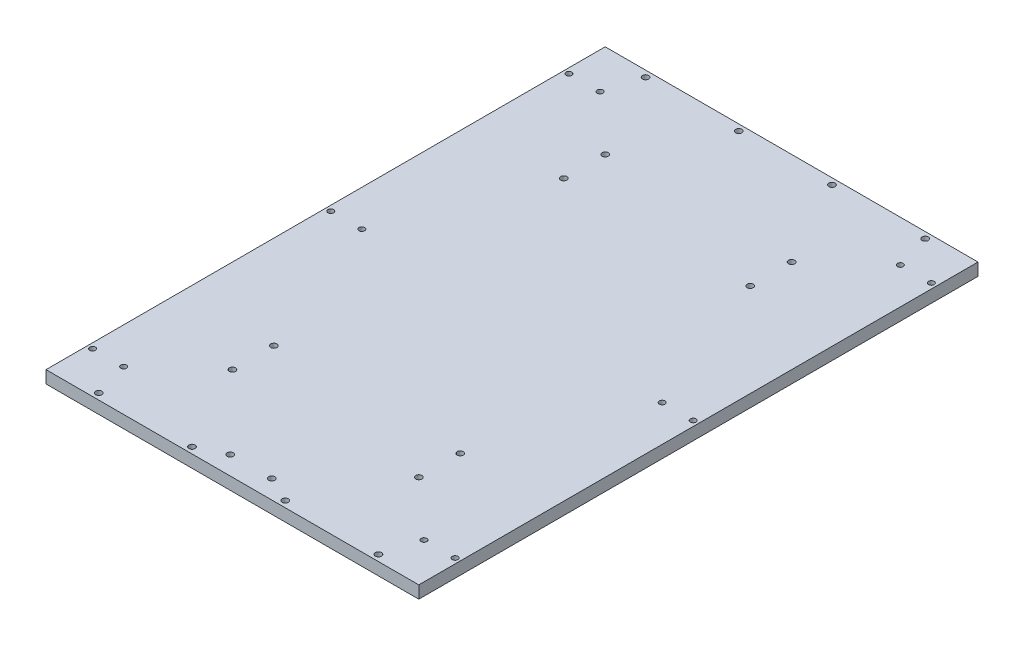
SolidWorks part; units mm, degrees
material "HDPE-green"
ref_plane "Front Plane" through (0, 0, 0) normal (0, 0, 1) x (1, 0, 0)
ref_plane "Top Plane" through (0, 0, 0) normal (0, 1, 0) x (1, 0, 0)
ref_plane "Right Plane" through (0, 0, 0) normal (1, 0, 0) x (0, 0, -1)
sketch "Sketch1" plane through (0, 0, 0) normal (0, 1, 0) x (1, 0, 0)
  line L1 (-180, -270) -> (180, -270)
  line L2 (-180, -270) -> (-180, 270)
  line L3 (-180, 270) -> (180, 270)
  line L4 (180, -270) -> (180, 270)
  line L5 (-180, -270) -> (180, 270) construction
  line L6 (-180, 270) -> (180, -270) construction
  point P0 (0, 0)
extrude "Boss-Extrude1" add sketch "Sketch1" along normal blind 12
sketch "Sketch2" plane through (0, 0, 0) normal (0, -1, 0) x (1, 0, 0)
  line L0 (-197.9035, 252) -> (209.2572, 252) construction
  line L1 (-180, 270) -> (180, 270) construction
  line L2 (0, 285.6833) -> (0, -295.2195) construction
  circle A0 centre (-20, 252) radius 3
  circle A1 centre (20, 252) radius 3
  dimension "D2" = 6
  dimension "D3" = 6
  dimension "D4" = 40
  dimension "D5" = 20
  dimension "D1" = 18
extrude "Cut-Extrude1" cut sketch "Sketch2" against normal up to next
sketch "Sketch3" plane through (0, 0, 0) normal (0, -1, 0) x (1, 0, 0)
  line L0 (-207.4551, 264) -> (223.7581, 264) construction
  line L1 (-180, 270) -> (180, 270) construction
  line L2 (180, 270) -> (180, -270) construction
  circle A0 centre (135, 264) radius 3
  dimension "D2" = 6
  dimension "D3" = 45
  dimension "D1" = 6
extrude "Cut-Extrude2" cut sketch "Sketch3" against normal up to next
pattern_linear "LPattern1" count 4 spacing 90 along (-1, 0, 0) of "Cut-Extrude2"
mirror "Mirror1" about plane through (0, 0, 0) normal (0, 0, 1) of "LPattern1", "Cut-Extrude2"
sketch "Sketch4" plane through (0, 12, 0) normal (0, 1, 0) x (1, 0, 0)
  line L0 (-160, 299.1839) -> (-160, -309.0635) construction
  line L1 (-180, 270) -> (-180, -270) construction
  line L2 (-188.5351, 0) -> (-124.846, 0) construction
  line L3 (-188.5351, 230) -> (-124.846, 230) construction
  line L4 (-129.91, -230) -> (-208.5429, -230) construction
  circle A0 centre (-175, 230) radius 2.75
  circle A1 centre (-145, 230) radius 2.75
  dimension "D4" = 5.5
  dimension "D5" = 5.5
  dimension "D7" = 15
  dimension "D1" = 20
  dimension "D2" = 230
  dimension "D3" = 230
  dimension "D6" = 15
extrude "Cut-Extrude3" cut sketch "Sketch4" against normal up to next
pattern_linear "LPattern2" count 3 spacing 230 along (0, 0, 1) of "Cut-Extrude3"
mirror "Mirror2" about plane through (0, 0, 0) normal (1, 0, 0) of "LPattern2", "Cut-Extrude3"
sketch "Sketch6" plane through (0, 12, 0) normal (0, 1, 0) x (1, 0, 0)
  line L0 (180, 270) -> (-180, 270) construction
  line L1 (-180, 270) -> (-180, -270) construction
  circle A0 centre (-90, 180) radius 3
  circle A1 centre (-90, 140) radius 3
  dimension "D1" = 6
  dimension "D2" = 6
  dimension "D3" = 90
  dimension "D4" = 90
  dimension "D5" = 40
  dimension "D6" = 90
extrude "Cut-Extrude4" cut sketch "Sketch6" against normal up to next
mirror "Mirror3" about plane through (0, 0, 0) normal (0, 0, 1) of "Cut-Extrude4"
mirror "Mirror4" about plane through (0, 0, 0) normal (1, 0, 0) of "Mirror3", "Cut-Extrude4"
